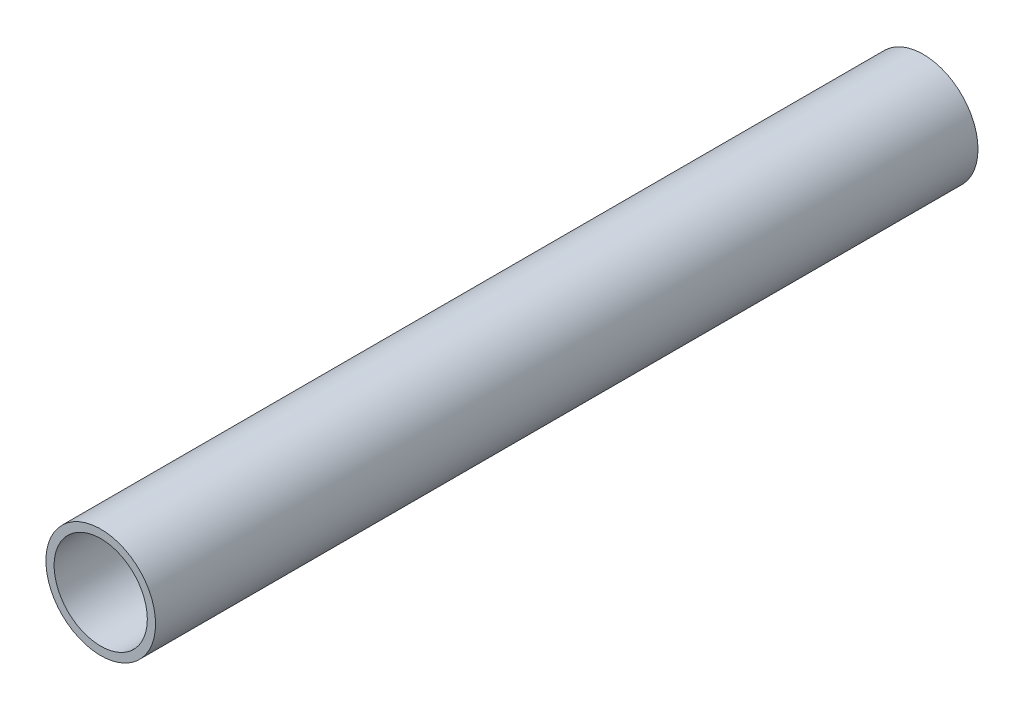
SolidWorks part; units mm, degrees
ref_plane "Front Plane" through (0, 0, 0) normal (0, 0, 1) x (1, 0, 0)
ref_plane "Top Plane" through (0, 0, 0) normal (0, 1, 0) x (1, 0, 0)
ref_plane "Right Plane" through (0, 0, 0) normal (1, 0, 0) x (0, 0, -1)
sketch "Sketch1" plane through (0, 0, 0) normal (0, 0, 1) x (1, 0, 0)
  circle A0 centre (0, 0) radius 20
  circle A1 centre (0, 0) radius 17
  dimension "D1" = 40
  dimension "D2" = 34
extrude "Boss-Extrude1" add sketch "Sketch1" along normal blind 300
